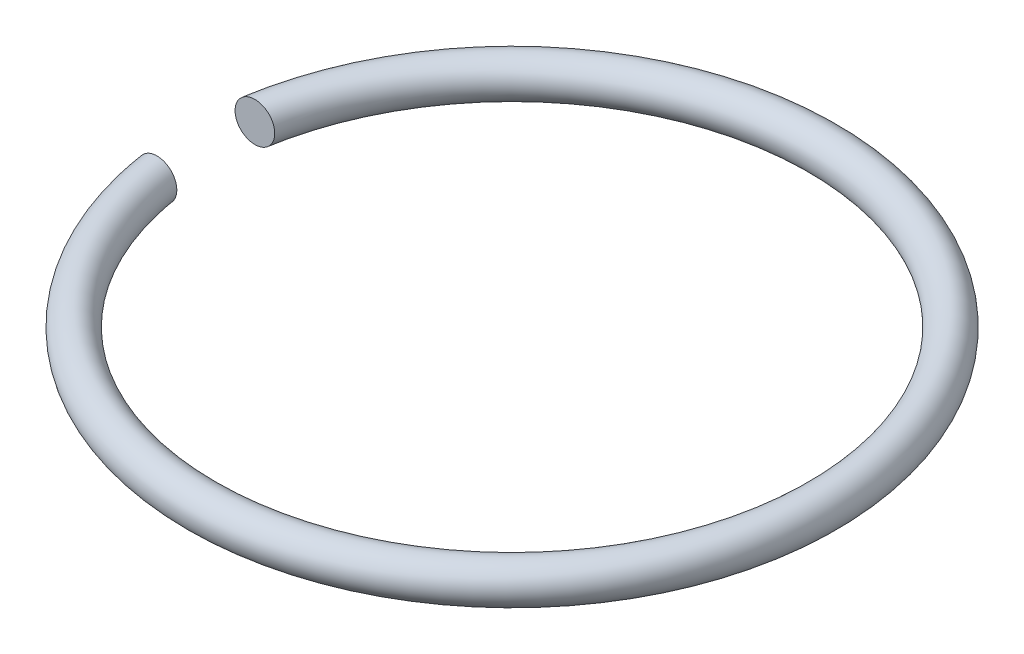
SolidWorks part; units mm, degrees
material "1.5805 (10NiCr5-4)"
ref_plane "Спереди" through (0, 0, 0) normal (0, 0, 1) x (1, 0, 0)
ref_plane "Сверху" through (0, 0, 0) normal (0, 1, 0) x (1, 0, 0)
ref_plane "Справа" through (0, 0, 0) normal (1, 0, 0) x (0, 0, -1)
sketch "Эскиз1" plane through (0, 0, 0) normal (0, 0, 1) x (1, 0, 0)
  line L0 (0, 0) -> (0, 5.376) construction
  circle A0 centre (-9.5, 0) radius 0.6
  dimension "D1" = 1.2
  dimension "D2" = 9.5
revolve "Повернуть1" add sketch "Эскиз1" angle 360 about L0
sketch "Эскиз2" plane through (0, 0, 0) normal (0, 1, 0) x (1, 0, 0)
  line L0 (0, 0) -> (-16.7656, 0) construction
  line L1 (-12.162, 1.5) -> (-7.1672, 1.5)
  line L2 (-12.162, 1.5) -> (-12.162, -1.5)
  line L3 (-12.162, -1.5) -> (-7.1672, -1.5)
  line L4 (-7.1672, 1.5) -> (-7.1672, -1.5)
  dimension "D1" = 1.5
  dimension "D2" = 1.5
extrude "Вырез-Вытянуть1" cut sketch "Эскиз2" against normal through all and the other way through all
ref_plane "Плоскость1" through (0, 0, 0) normal (0, -1, 0) x (-1, 0, 0)
